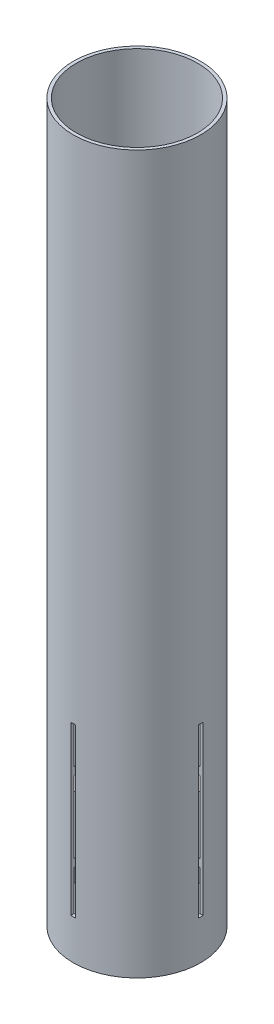
SolidWorks part; units mm, degrees
ref_plane "Front Plane" through (0, 0, 0) normal (0, 0, 1) x (1, 0, 0)
ref_plane "Top Plane" through (0, 0, 0) normal (0, 1, 0) x (1, 0, 0)
ref_plane "Right Plane" through (0, 0, 0) normal (1, 0, 0) x (0, 0, -1)
sketch "Sketch1" plane through (0, 0, 0) normal (0, 1, 0) x (1, 0, 0)
  circle A0 centre (0, 0) radius 40
  circle A1 centre (0, 0) radius 38
  dimension "D1" = 80
  dimension "D2" = 76
extrude "Boss-Extrude1" add sketch "Sketch1" along normal blind 450
ref_plane "Plane1" through (-40, 0, 0) normal (-1, 0, 0) x (0, 0, 1)
sketch "Sketch2" plane through (-40, 0, 0) normal (-1, 0, 0) x (0, 0, 1)
  line L1 (1.5, 130) -> (-1.5, 130)
  line L2 (1.5, 130) -> (1.5, 25)
  line L3 (1.5, 25) -> (-1.5, 25)
  line L4 (-1.5, 130) -> (-1.5, 25)
  line L5 (1.5, 130) -> (-1.5, 25) construction
  line L6 (1.5, 25) -> (-1.5, 130) construction
  point P0 (0, 77.5)
  dimension "D1" = 25
  dimension "D2" = 3
  dimension "D3" = 105
sketch "Sketch3" plane through (0, 0, 0) normal (0, -1, 0) x (1, 0, 0)
  circle A0 centre (0, 0) radius 38 construction
  circle A1 centre (0, 0) radius 40
  circle A2 centre (0, 0) radius 40
  circle A3 centre (0, 0) radius 38
  circle A4 centre (0, 0) radius 20
  circle M3 centre (0, 0) radius 38
  dimension "D2" = 40
  dimension "D1" = 0
extrude "Boss-Extrude2" add sketch "Sketch3" against normal blind 5 contours A4 M3
ref_plane "Plane2" through (0, 0, 0) normal (0, 0, 1) x (1, 0, 0)
pattern_linear "LPattern1" count 5 spacing 50 along (0, 1, 0) of "Boss-Extrude2"
ref_plane "Plane3" through (0, 255, 0) normal (0, 1, 0) x (1, 0, 0)
sketch "Sketch6" plane through (0, 255, 0) normal (0, 1, 0) x (1, 0, 0)
  circle A8 centre (0, 0) radius 38
  circle A16 centre (0, 0) radius 38
  dimension "D1" = 0
extrude "Boss-Extrude3" add sketch "Sketch6" against normal blind 10
sketch "Sketch9" plane through (0, 50, 0) normal (0, -1, 0) x (1, 0, 0)
  line L0 (-29.9578, 1.5) -> (-29.9578, -1.5)
  line L1 (-1.5, -36.9696) -> (-1.5, -29.9578)
  line L2 (1.5, -36.9696) -> (1.5, -29.9578)
  line L3 (-1.5, -29.9578) -> (1.5, -29.9578) construction
  line L4 (-1.5, -29.9578) -> (1.5, -29.9578)
  line L5 (-36.9696, -1.5) -> (-29.9578, -1.5)
  line L6 (-36.9696, 1.5) -> (-29.9578, 1.5)
  line L7 (1.5, 29.9578) -> (-1.5, 29.9578)
  line L8 (-1.5, 36.9696) -> (-1.5, 29.9578)
  line L9 (1.5, 36.9696) -> (1.5, 29.9578)
  line L10 (29.9578, -1.5) -> (29.9578, 1.5)
  line L11 (36.9696, 1.5) -> (29.9578, 1.5)
  line L12 (36.9696, -1.5) -> (29.9578, -1.5)
  arc A5 (-36.9696, 1.5) -> (-36.9696, -1.5) centre (0, 0) ccw
  arc A7 (1.5, 36.9696) -> (-1.5, 36.9696) centre (0, 0) ccw
  arc A8 (-1.5, -36.9696) -> (1.5, -36.9696) centre (0, 0) ccw
  arc A9 (36.9696, -1.5) -> (36.9696, 1.5) centre (0, 0) ccw
  point P22 (0, 0)
  dimension "D3" = 74
  dimension "D1" = 3
  dimension "D2" = 4
sketch "Sketch10" plane through (0, 50, 0) normal (0, -1, 0) x (1, 0, 0)
  line L0 (-1.5, 29.9578) -> (-1.5, 36.9696)
  line L1 (1.5, 29.9578) -> (1.5, 36.9696)
  line L2 (29.9578, 1.5) -> (36.9696, 1.5)
  line L3 (29.9578, -1.5) -> (36.9696, -1.5)
  line L4 (-1.5, -29.9578) -> (-1.5, -36.9696)
  line L5 (1.5, -29.9578) -> (1.5, -36.9696)
  line L6 (-29.9578, -1.5) -> (-36.9696, -1.5)
  line L7 (-29.9578, 1.5) -> (-36.9696, 1.5)
  line L8 (-29.9578, -1.5) -> (-29.9578, 1.5)
  line L9 (-1.5, 29.9578) -> (1.5, 29.9578)
  line L10 (29.9578, 1.5) -> (29.9578, -1.5)
  line L11 (1.5, -29.9578) -> (-1.5, -29.9578)
  line L13 (-29.9578, -1.5) -> (-36.9696, -1.5)
  line L15 (-29.9578, 0) -> (-40, 0) construction
  arc A4 (-1.5, -36.9696) -> (1.5, -36.9696) centre (0, 0) ccw
  arc A5 (36.9696, -1.5) -> (36.9696, 1.5) centre (0, 0) ccw
  arc A6 (-36.9696, 1.5) -> (-36.9696, -1.5) centre (0, 0) ccw
  arc A7 (1.5, 36.9696) -> (-1.5, 36.9696) centre (0, 0) ccw
  circle A15 centre (0, 0) radius 40 construction
  dimension "D1" = 74
  dimension "D2" = 10.0422
extrude "Cut-Extrude6" cut sketch "Sketch2" against normal blind 10
pattern_circular "CirPattern6" count 4 over 360 about axis through (0, 0, 0) along (0, 1, 0) of "Cut-Extrude6"
equation "\"Dint\"=76"
equation "\"Dext\"=80"
equation "\"Length\" = 610"
equation "\"D\"=25"
equation "\"D1@Sketch2\"=\"D\""
equation "\"Fins Thick\"=3"
equation "\"D2@Sketch2\"=\"Fins Thick\""
equation "\"FinsLength\"=105"
equation "\"D3@Sketch2\"=\"FinsLength\""
equation "\"Lenght tube 3\"= 450"
equation "\"D1@Boss-Extrude1\"=\"Lenght tube 3\""
equation "\"D betwen disc\"=50"
equation "\"D3@LPattern1\"=\"D betwen disc\""
equation "\"ancho del reten del motor\"=10"
equation "\"D1@Boss-Extrude3\"=\"ancho del reten del motor\""
equation "\"grosor braso aleta\"=10"
equation "\"largpo braso aleta\"=10"
equation "\"D1@Cut-Extrude6\"=\"largpo braso aleta\""
